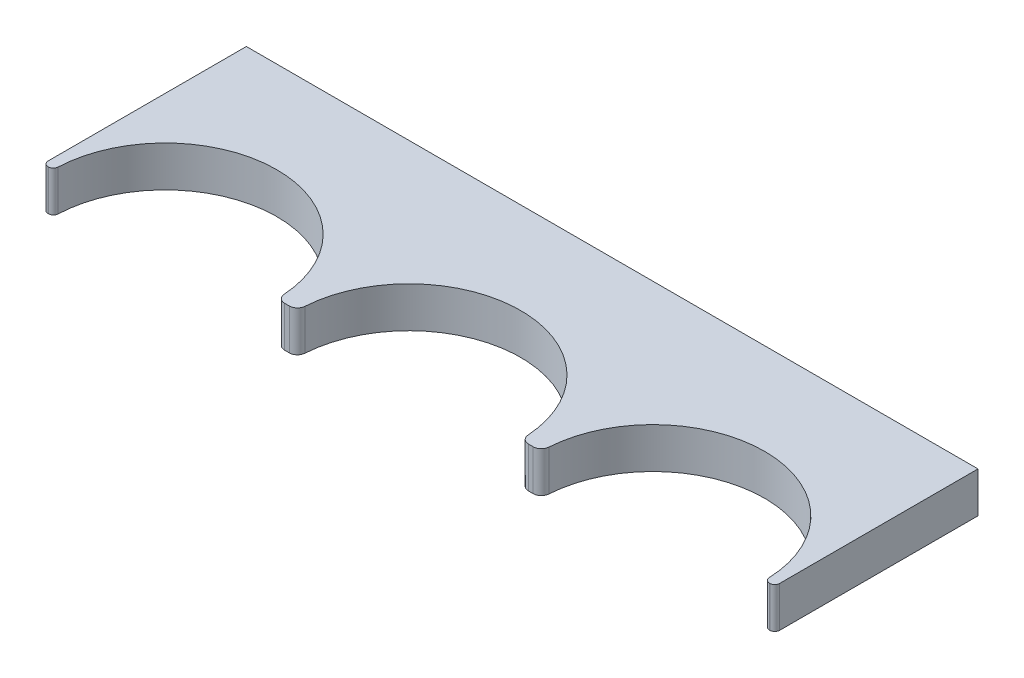
SolidWorks part; units mm, degrees
ref_plane "Plan de face" through (0, 0, 0) normal (0, 0, 1) x (1, 0, 0)
ref_plane "Plan de dessus" through (0, 0, 0) normal (0, 1, 0) x (1, 0, 0)
ref_plane "Plan de droite" through (0, 0, 0) normal (1, 0, 0) x (0, 0, -1)
sketch "Esquisse1" plane through (0, 0, 0) normal (0, 1, 0) x (1, 0, 0)
  line L0 (-88.6749, -25) -> (-88.8, -25)
  line L1 (88.8, -25) -> (88.6749, -25)
  line L2 (90, -23.8) -> (90, 25)
  line L3 (90, 25) -> (-90, 25)
  line L4 (-90, -23.8) -> (-90, 25)
  line L5 (90, -25) -> (-90, 25) construction
  line L6 (90, 25) -> (-90, -25) construction
  line L7 (-90, -25) -> (90, -25) construction
  line L8 (-29.4321, -25) -> (-30.5679, -25)
  line L9 (30.5679, -25) -> (29.4321, -25)
  arc A0 (-32.5633, -23.1356) -> (-87.476, -23.8502) centre (-60, -25) ccw
  arc A1 (27.4367, -23.1356) -> (-27.4367, -23.1356) centre (0, -25) ccw
  arc A2 (87.476, -23.8502) -> (32.5633, -23.1356) centre (60, -25) ccw
  arc A5 (88.8, -25) -> (90, -23.8) centre (88.8, -23.8) ccw
  arc A6 (88.6749, -25) -> (87.476, -23.8502) centre (88.6749, -23.8) cw
  arc A7 (-88.8, -25) -> (-90, -23.8) centre (-88.8, -23.8) cw
  arc A8 (-88.6749, -25) -> (-87.476, -23.8502) centre (-88.6749, -23.8) ccw
  arc A9 (30.5679, -25) -> (32.5633, -23.1356) centre (30.5679, -23) ccw
  arc A10 (27.4367, -23.1356) -> (29.4321, -25) centre (29.4321, -23) ccw
  arc A11 (-29.4321, -25) -> (-27.4367, -23.1356) centre (-29.4321, -23) ccw
  arc A12 (-32.5633, -23.1356) -> (-30.5679, -25) centre (-30.5679, -23) ccw
  point P0 (0, 0)
  point P29 (32.5, -25)
  point P32 (27.5, -25)
  point P35 (-27.5, -25)
  point P38 (-32.5, -25)
  dimension "D4" = 55
  dimension "D7" = 1.2
  dimension "D8" = 2
  dimension "D1" = 180
  dimension "D2" = 50
  dimension "D3" = 3
  dimension "D5" = 30
  dimension "D6" = 30
extrude "Boss.-Extru.1" add sketch "Esquisse1" along normal blind 10
